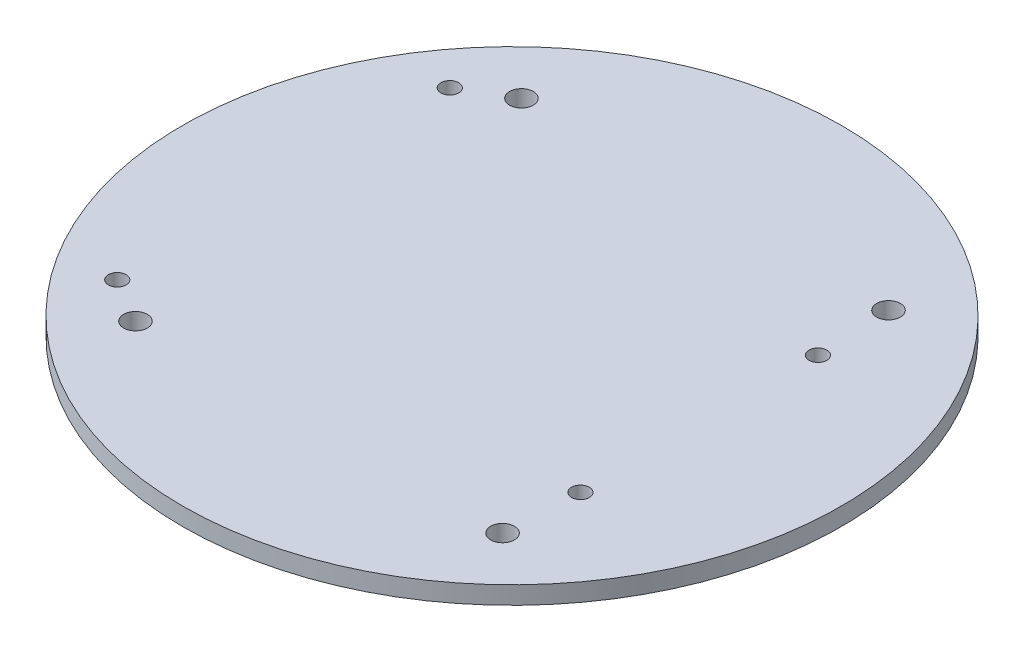
SolidWorks part; units mm, degrees
material "Acrylic (Medium-high impact)"
ref_plane "Front" through (0, 0, 0) normal (0, 0, 1) x (1, 0, 0)
ref_plane "Top" through (0, 0, 0) normal (0, 1, 0) x (1, 0, 0)
ref_plane "Right" through (0, 0, 0) normal (1, 0, 0) x (0, 0, -1)
sketch "Sketch7" plane through (0, 0, 0) normal (0, 1, 0) x (1, 0, 0)
  circle A0 centre (0, 0) radius 55.5
  dimension "D1" = 111
extrude "Boss-Extrude1" add sketch "Sketch7" along normal blind 3
sketch "Sketch9" plane through (0, 3, 0) normal (0, 1, 0) x (1, 0, 0)
  point P0 (-38.4763, 28)
  point P1 (-38.4763, -28)
  point P3 (31.5237, -20)
  point P5 (31.5237, 20)
hole_wizard "Ø3.0mm Transitional Dowel Hole1" positions "Sketch10" profile "Sketch11" hole size "Ø3.0" standard "ANSI Metric"
sketch "Sketch10" plane through (0, 3, 0) normal (0, 1, 0) x (1, 0, 0)
  point P0 (-38.4763, 28)
  point P3 (31.5237, 20)
  point P6 (31.5237, -20)
  point P9 (-38.4763, -28)
sketch "Sketch11" plane through (-38.4763, 3, -28) normal (1, 0, 0) x (0, 0, 1)
  line L0 (0, 0) -> (0, 26.3013)
  line L1 (0, 26.3013) -> (1.5, 25.4)
  line L2 (1.5, 25.4) -> (1.5, 0)
  line L5 (1.5, 0) -> (0, 0)
  line L10 (0, 26.3013) -> (-1.5, 25.4) construction
  line L11 (0, -6.35) -> (0, 107.95) construction
  dimension "Hole Dia." = 3
  dimension "Hole Depth" = 25.4
  dimension "Drill Angle" = 118
hole_wizard "Ø4.0mm Dowel Hole1" positions "Sketch12" profile "Sketch13" hole size "Ø4.0" standard "ANSI Metric"
sketch "Sketch12" plane through (0, 3, 0) normal (0, 1, 0) x (1, 0, 0)
  point P0 (-30.9068, 32.5)
  point P3 (30.9068, 32.5)
  point P6 (30.9068, -32.5)
  point P9 (-30.9068, -32.5)
sketch "Sketch13" plane through (-30.9068, 3, -32.5) normal (1, 0, 0) x (0, 0, 1)
  line L0 (0, 0) -> (0, 26.6017)
  line L1 (0, 26.6017) -> (2, 25.4)
  line L2 (2, 25.4) -> (2, 0)
  line L5 (2, 0) -> (0, 0)
  line L10 (0, 26.6017) -> (-2, 25.4) construction
  line L11 (0, -6.35) -> (0, 107.95) construction
  dimension "Hole Dia." = 4
  dimension "Hole Depth" = 25.4
  dimension "Drill Angle" = 118
